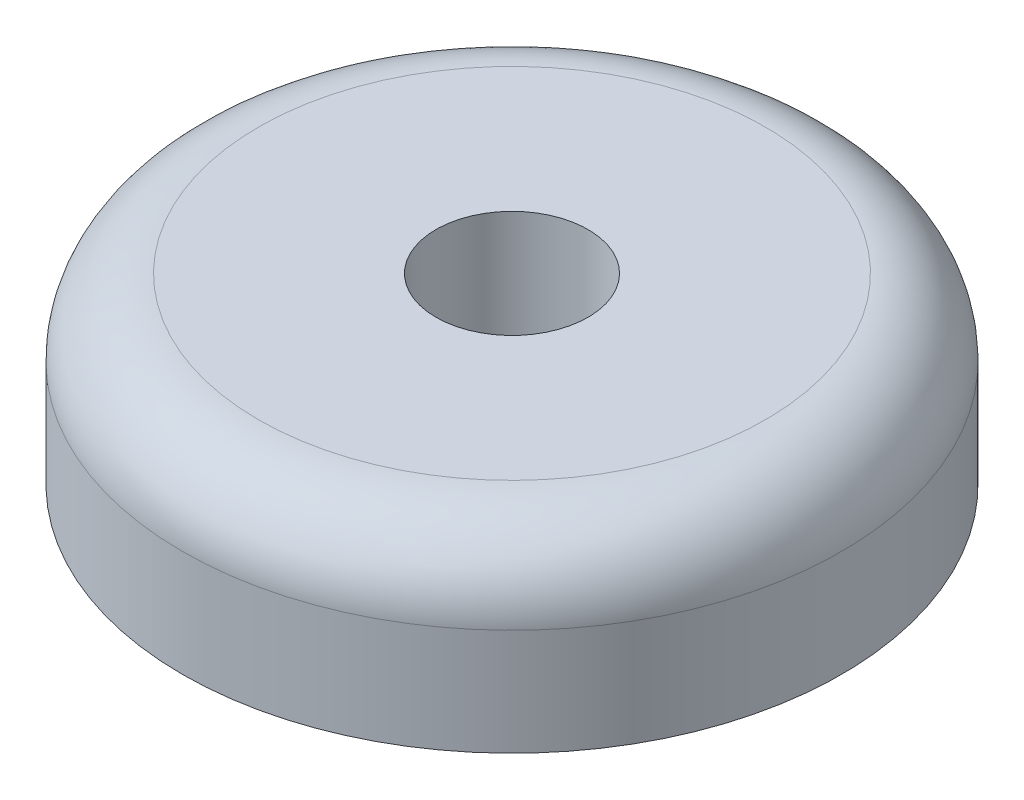
SolidWorks part; units mm, degrees
ref_plane "Front Plane" through (0, 0, 0) normal (0, 0, 1) x (1, 0, 0)
ref_plane "Top Plane" through (0, 0, 0) normal (0, 1, 0) x (1, 0, 0)
ref_plane "Right Plane" through (0, 0, 0) normal (1, 0, 0) x (0, 0, -1)
sketch "Sketch1" plane through (0, 0, 0) normal (0, 1, 0) x (1, 0, 0)
  circle A0 centre (0, 0) radius 6.5
  circle A1 centre (0, 0) radius 1.5
  dimension "D1" = 13
  dimension "D2" = 3
extrude "Boss-Extrude1" add sketch "Sketch1" along normal blind 3.6
fillet "Fillet2" radius 1.5 1 edges at (0, 3.6, 6.5)
